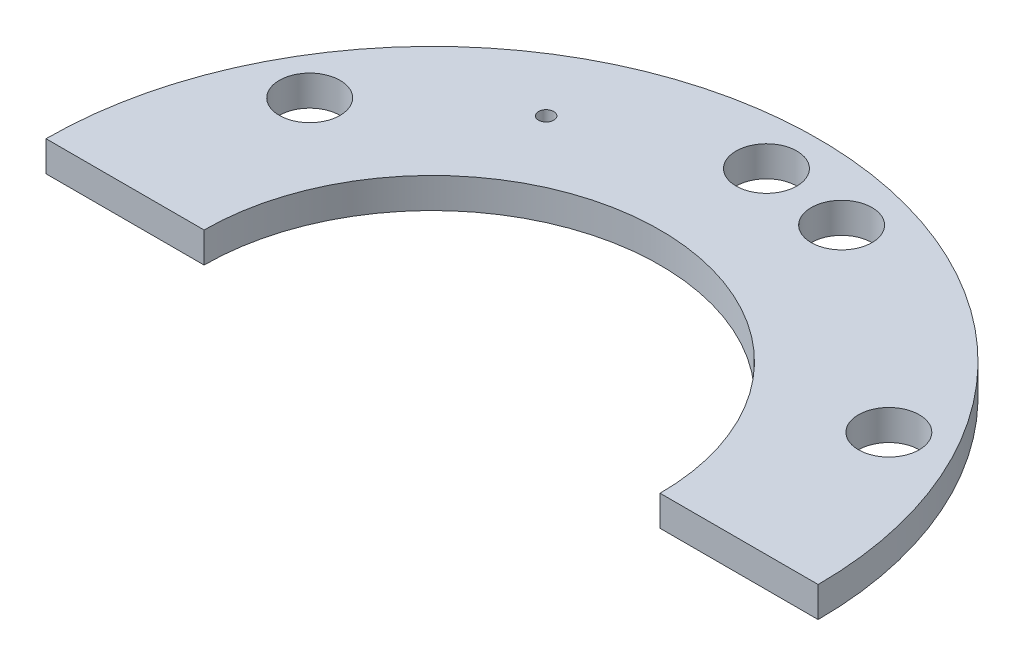
SolidWorks part; units mm, degrees
material "ABS"
ref_plane "Front Plane" through (0, 0, 0) normal (0, 0, 1) x (1, 0, 0)
ref_plane "Top Plane" through (0, 0, 0) normal (0, 1, 0) x (1, 0, 0)
ref_plane "Right Plane" through (0, 0, 0) normal (1, 0, 0) x (0, 0, -1)
sketch "Sketch1" plane through (0, 0, 0) normal (0, 1, 0) x (1, 0, 0)
  circle A0 centre (0, 0) radius 12.7
  dimension "D1" = 25.4
extrude "Boss-Extrude1" add sketch "Sketch1" along normal blind 1
sketch "Sketch19" plane through (0, 1, 0) normal (0, 1, 0) x (1, 0, 0)
  circle A0 centre (0, 11) radius 1
  circle A1 centre (9.5263, 5.5) radius 1
  circle A2 centre (9.5263, -5.5) radius 1
  circle A3 centre (0, -11) radius 1
  circle A4 centre (-9.5263, -5.5) radius 1
  circle A5 centre (-9.5263, 5.5) radius 1
  point P13 (0, 0)
  dimension "D1" = 2
  dimension "D2" = 11
  dimension "D3" = 6
extrude "Cut-Extrude1" cut sketch "Sketch19" against normal through all both and the other way through all
sketch "Sketch20" plane through (0, 1, 0) normal (0, 1, 0) x (1, 0, 0)
  circle A0 centre (0, 0) radius 7.5
  dimension "D1" = 15
extrude "Cut-Extrude2" cut sketch "Sketch20" against normal through all both and the other way through all
sketch "Sketch21" plane through (0, 0, 0) normal (0, 0, 1) x (1, 0, 0)
  line L1 (-36.7533, 32.3113) -> (29.1209, 32.3113)
  line L2 (-36.7533, 32.3113) -> (-36.7533, -19.668)
  line L3 (-36.7533, -19.668) -> (29.1209, -19.668)
  line L4 (29.1209, 32.3113) -> (29.1209, -19.668)
extrude "Cut-Extrude3" cut sketch "Sketch21" along normal through all
sketch "Sketch22" plane through (0, 1, 0) normal (0, 1, 0) x (1, 0, 0)
  line L0 (-9.5263, 5.5) -> (0, 11)
  line L1 (0, 0) -> (-5.125, 8.8768) construction
  circle A0 centre (-5.125, 8.8768) radius 0.25
  dimension "D1" = 0.5
  dimension "D2" = 10.25
extrude "Cut-Extrude4" cut sketch "Sketch22" against normal through all both and the other way through all
sketch "Sketch23" plane through (0, 1, 0) normal (0, 1, 0) x (1, 0, 0)
  line L0 (0, 0) -> (-5.125, 8.8768) construction
  line L1 (-5.125, 8.8768) -> (0, 0) construction
  line L2 (0, 0) -> (4.5783, 17.0863) construction
  circle A0 centre (2.847, 10.6252) radius 1
  dimension "D1" = 2
  dimension "D2" = 11
  dimension "D3" = 45
extrude "Cut-Extrude5" cut sketch "Sketch23" against normal through all both and the other way through all
